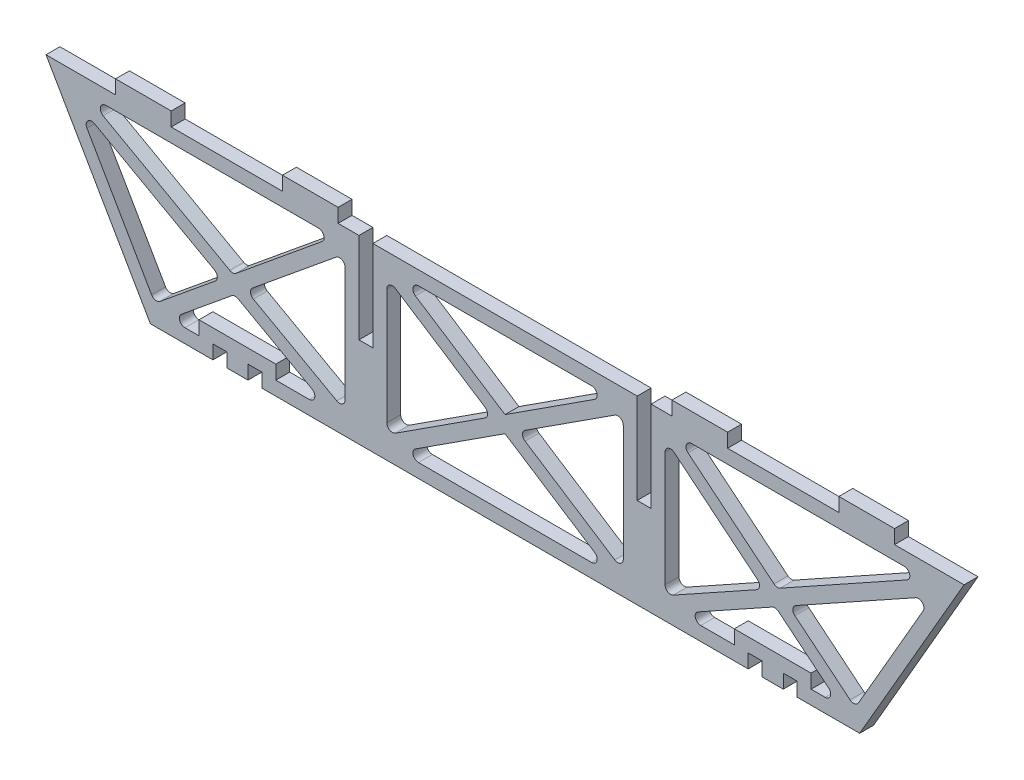
SolidWorks part; units mm, degrees
ref_plane "Front Plane" through (0, 0, 0) normal (0, 0, 1) x (1, 0, 0)
ref_plane "Top Plane" through (0, 0, 0) normal (0, 1, 0) x (1, 0, 0)
ref_plane "Right Plane" through (0, 0, 0) normal (1, 0, 0) x (0, 0, -1)
sketch "Sketch1" plane through (0, 0, 0) normal (0, 0, 1) x (1, 0, 0)
  line L0 (47.6603, 0) -> (76.2, 0)
  line L1 (0, 0) -> (0, 82.55) construction
  line L2 (0, 82.55) -> (31.75, 82.55)
  line L3 (98.552, 0) -> (320.548, 0)
  line L4 (0, 82.55) -> (47.6603, 0)
  line L5 (155.575, 67.7494) -> (155.575, 14.8006)
  line L6 (170.0204, 6.35) -> (249.0796, 6.35)
  line L7 (0, 0) -> (47.6603, 0) construction
  line L8 (209.55, 82.55) -> (209.55, 0) construction
  line L9 (31.75, 82.55) -> (31.75, 88.9)
  line L10 (31.75, 88.9) -> (57.15, 88.9)
  line L11 (57.15, 88.9) -> (57.15, 82.55)
  line L12 (57.15, 82.55) -> (107.95, 82.55)
  line L13 (107.95, 82.55) -> (107.95, 88.9)
  line L14 (107.95, 88.9) -> (133.35, 88.9)
  line L15 (133.35, 88.9) -> (133.35, 82.55)
  line L16 (133.35, 82.55) -> (142.875, 82.55)
  line L17 (51.3264, 6.35) -> (136.525, 76.2) construction
  line L18 (136.525, 6.35) -> (10.9985, 76.2) construction
  line L19 (52.0316, 11.0337) -> (77.262, 31.7189)
  line L20 (61.8282, 10.8542) -> (84.7804, 29.6715)
  line L21 (26.0814, 71.4405) -> (83.9206, 39.2555)
  line L22 (22.1181, 66.379) -> (76.8867, 35.9027)
  line L23 (86.766, 39.5108) -> (126.0232, 71.6958)
  line L24 (94.2844, 37.4634) -> (132.3746, 68.6917)
  line L25 (76.2, 0) -> (76.2, 6.35)
  line L26 (76.2, 6.35) -> (82.55, 6.35)
  line L27 (82.55, 6.35) -> (82.55, 0)
  line L28 (82.55, 0) -> (92.202, 0)
  line L29 (92.202, 0) -> (92.202, 6.35)
  line L30 (92.202, 6.35) -> (98.552, 6.35)
  line L31 (98.552, 6.35) -> (98.552, 0)
  line L32 (87.6258, 29.9268) -> (121.4421, 11.1095)
  line L33 (94.6597, 33.2797) -> (132.7499, 12.0841)
  line L34 (14.0893, 70.8467) -> (10.9985, 76.2) construction
  line L35 (10.9985, 76.2) -> (17.5282, 76.2) construction
  line L36 (49.7176, 9.1366) -> (51.3264, 6.35) construction
  line L37 (56.3342, 6.35) -> (51.3264, 6.35) construction
  line L38 (129.9954, 6.35) -> (136.525, 6.35) construction
  line L39 (136.525, 9.9835) -> (136.525, 6.35) construction
  line L40 (146.05, 82.55) -> (146.05, 0) construction
  line L41 (142.875, 82.55) -> (142.875, 41.275)
  line L42 (142.875, 41.275) -> (149.225, 41.275)
  line L43 (149.225, 82.55) -> (149.225, 41.275)
  line L44 (149.225, 82.55) -> (269.875, 82.55)
  line L45 (131.5172, 76.2) -> (136.525, 76.2) construction
  line L46 (142.875, 82.55) -> (149.225, 82.55) construction
  line L47 (136.525, 76.2) -> (136.525, 72.0944) construction
  line L48 (209.55, 41.275) -> (155.575, 6.35) construction
  line L49 (209.55, 41.275) -> (155.575, 76.2) construction
  line L50 (159.4949, 69.8819) -> (200.4099, 43.4075)
  line L51 (168.6406, 71.5275) -> (209.55, 45.0567)
  line L52 (159.4949, 12.6681) -> (200.4099, 39.1425)
  line L53 (168.6406, 11.0225) -> (209.55, 37.4933)
  line L54 (170.0204, 76.2) -> (249.0796, 76.2)
  line L55 (18.6834, 62.8895) -> (48.2215, 11.728)
  line L56 (63.4386, 6.35) -> (69.85, 6.35)
  line L57 (69.85, 6.35) -> (69.85, 12.7)
  line L58 (69.85, 12.7) -> (104.902, 12.7)
  line L59 (155.575, 14.8006) -> (155.575, 6.35) construction
  line L60 (104.902, 6.35) -> (120.207, 6.35)
  line L61 (155.575, 6.35) -> (170.0204, 6.35) construction
  line L62 (155.575, 67.7494) -> (155.575, 76.2) construction
  line L63 (155.575, 76.2) -> (170.0204, 76.2) construction
  line L64 (269.875, 82.55) -> (269.875, 41.275)
  line L65 (282.575, 66.7274) -> (282.575, 14.3036)
  line L66 (391.7835, 76.2) -> (294.6872, 76.2)
  line L67 (314.198, 12.7) -> (314.198, 6.35)
  line L68 (314.198, 6.35) -> (298.893, 6.35)
  line L69 (349.25, 12.7) -> (314.198, 12.7)
  line L70 (349.25, 6.35) -> (349.25, 12.7)
  line L71 (355.6614, 6.35) -> (349.25, 6.35)
  line L72 (400.4166, 62.8895) -> (370.8785, 11.728)
  line L73 (104.902, 12.7) -> (104.902, 6.35)
  line L74 (250.4594, 11.0225) -> (209.55, 37.4933)
  line L75 (259.6051, 12.6681) -> (218.6901, 39.1425)
  line L76 (250.4594, 71.5275) -> (209.55, 45.0567)
  line L77 (259.6051, 69.8819) -> (218.6901, 43.4075)
  line L78 (276.225, 41.275) -> (269.875, 41.275)
  line L79 (276.225, 82.55) -> (276.225, 41.275)
  line L80 (324.4403, 33.2797) -> (286.3501, 12.0841)
  line L81 (331.4742, 29.9268) -> (297.6579, 11.1095)
  line L82 (320.548, 6.35) -> (320.548, 0)
  line L83 (27.3165, 76.2) -> (124.4128, 76.2)
  line L84 (326.898, 6.35) -> (320.548, 6.35)
  line L85 (326.898, 0) -> (326.898, 6.35)
  line L86 (336.55, 0) -> (326.898, 0)
  line L87 (336.55, 6.35) -> (336.55, 0)
  line L88 (342.9, 6.35) -> (336.55, 6.35)
  line L89 (342.9, 0) -> (342.9, 6.35)
  line L90 (324.8156, 37.4634) -> (286.7254, 68.6917)
  line L91 (332.334, 39.5108) -> (293.0768, 71.6958)
  line L92 (396.9819, 66.379) -> (342.2133, 35.9027)
  line L93 (393.0186, 71.4405) -> (335.1794, 39.2555)
  line L94 (357.2718, 10.8542) -> (334.3196, 29.6715)
  line L95 (367.0684, 11.0337) -> (341.838, 31.7189)
  line L96 (285.75, 82.55) -> (276.225, 82.55)
  line L97 (285.75, 88.9) -> (285.75, 82.55)
  line L98 (311.15, 88.9) -> (285.75, 88.9)
  line L99 (311.15, 82.55) -> (311.15, 88.9)
  line L100 (361.95, 82.55) -> (311.15, 82.55)
  line L101 (361.95, 88.9) -> (361.95, 82.55)
  line L102 (387.35, 88.9) -> (361.95, 88.9)
  line L103 (387.35, 82.55) -> (387.35, 88.9)
  line L104 (263.525, 67.7494) -> (263.525, 14.8006)
  line L105 (371.4397, 0) -> (342.9, 0)
  line L106 (419.1, 82.55) -> (371.4397, 0)
  line L107 (419.1, 82.55) -> (387.35, 82.55)
  line L111 (136.525, 66.7274) -> (136.525, 14.3036)
  arc A0 (27.3165, 76.2) -> (26.0814, 71.4405) centre (27.3165, 73.66) ccw
  arc A1 (18.6834, 62.8895) -> (22.1181, 66.379) centre (20.8831, 64.1595) cw
  arc A2 (52.0316, 11.0337) -> (48.2215, 11.728) centre (50.4212, 12.998) cw
  arc A3 (63.4386, 6.35) -> (61.8282, 10.8542) centre (63.4386, 8.89) cw
  arc A4 (120.207, 6.35) -> (121.4421, 11.1095) centre (120.207, 8.89) ccw
  arc A5 (136.525, 66.7274) -> (132.3746, 68.6917) centre (133.985, 66.7274) ccw
  arc A6 (124.4128, 76.2) -> (126.0232, 71.6958) centre (124.4128, 73.66) cw
  arc A7 (136.525, 14.3036) -> (132.7499, 12.0841) centre (133.985, 14.3036) cw
  arc A8 (86.766, 39.5108) -> (83.9206, 39.2555) centre (85.1556, 41.475) cw
  arc A9 (76.8867, 35.9027) -> (77.262, 31.7189) centre (75.6516, 33.6832) cw
  arc A10 (87.6258, 29.9268) -> (84.7804, 29.6715) centre (86.3908, 27.7073) ccw
  arc A11 (94.2844, 37.4634) -> (94.6597, 33.2797) centre (95.8948, 35.4992) ccw
  arc A12 (155.575, 67.7494) -> (159.4949, 69.8819) centre (158.115, 67.7494) cw
  arc A13 (155.575, 14.8006) -> (159.4949, 12.6681) centre (158.115, 14.8006) ccw
  arc A14 (170.0204, 6.35) -> (168.6406, 11.0225) centre (170.0204, 8.89) cw
  arc A15 (200.4099, 43.4075) -> (200.4099, 39.1425) centre (199.03, 41.275) cw
  arc A16 (170.0204, 76.2) -> (168.6406, 71.5275) centre (170.0204, 73.66) ccw
  arc A17 (249.0796, 76.2) -> (250.4594, 71.5275) centre (249.0796, 73.66) cw
  arc A18 (218.6901, 43.4075) -> (218.6901, 39.1425) centre (220.07, 41.275) ccw
  arc A19 (249.0796, 6.35) -> (250.4594, 11.0225) centre (249.0796, 8.89) ccw
  arc A20 (263.525, 14.8006) -> (259.6051, 12.6681) centre (260.985, 14.8006) cw
  arc A21 (263.525, 67.7494) -> (259.6051, 69.8819) centre (260.985, 67.7494) ccw
  arc A22 (324.8156, 37.4634) -> (324.4403, 33.2797) centre (323.2052, 35.4992) cw
  arc A23 (331.4742, 29.9268) -> (334.3196, 29.6715) centre (332.7092, 27.7073) cw
  arc A24 (342.2133, 35.9027) -> (341.838, 31.7189) centre (343.4484, 33.6832) ccw
  arc A25 (332.334, 39.5108) -> (335.1794, 39.2555) centre (333.9444, 41.475) ccw
  arc A26 (282.575, 14.3036) -> (286.3501, 12.0841) centre (285.115, 14.3036) ccw
  arc A27 (294.6872, 76.2) -> (293.0768, 71.6958) centre (294.6872, 73.66) ccw
  arc A28 (282.575, 66.7274) -> (286.7254, 68.6917) centre (285.115, 66.7274) cw
  arc A29 (298.893, 6.35) -> (297.6579, 11.1095) centre (298.893, 8.89) cw
  arc A30 (355.6614, 6.35) -> (357.2718, 10.8542) centre (355.6614, 8.89) ccw
  arc A31 (367.0684, 11.0337) -> (370.8785, 11.728) centre (368.6788, 12.998) ccw
  arc A32 (400.4166, 62.8895) -> (396.9819, 66.379) centre (398.2169, 64.1595) ccw
  arc A33 (391.7835, 76.2) -> (393.0186, 71.4405) centre (391.7835, 73.66) cw
  point P47 (146.05, 41.275)
  point P157 (209.55, 76.2)
  point P175 (209.55, 6.35)
  point P176 (273.05, 41.275)
  dimension "D24" = 6.35
  dimension "D29" = 2.54
  dimension "D2" = 82.55
  dimension "D3" = 60
  dimension "D4" = 6.35
  dimension "D5" = 25.4
  dimension "D6" = 63.5
  dimension "D7" = 25.4
  dimension "D8" = 41.275
  dimension "D9" = 6.35
  dimension "D10" = 6.35
  dimension "D11" = 76.2
  dimension "D12" = 9.652
  dimension "D13" = 6.35
  dimension "D14" = 209.55
  dimension "D15" = 76.2
  dimension "D16" = 152.4
  dimension "D17" = 6.35
  dimension "D18" = 6.35
  dimension "D19" = 6.35
  dimension "D20" = 6.35
  dimension "D21" = 6.35
  dimension "D22" = 6.35
  dimension "D23" = 6.35
  dimension "D25" = 3.175
  dimension "D26" = 3.175
  dimension "D27" = 3.175
  dimension "D28" = 3.175
  dimension "D30" = 3.175
  dimension "D31" = 3.175
  dimension "D33" = 3.175
  dimension "D34" = 3.175
extrude "Extrude2" add sketch "Sketch1" along normal blind 6.35
